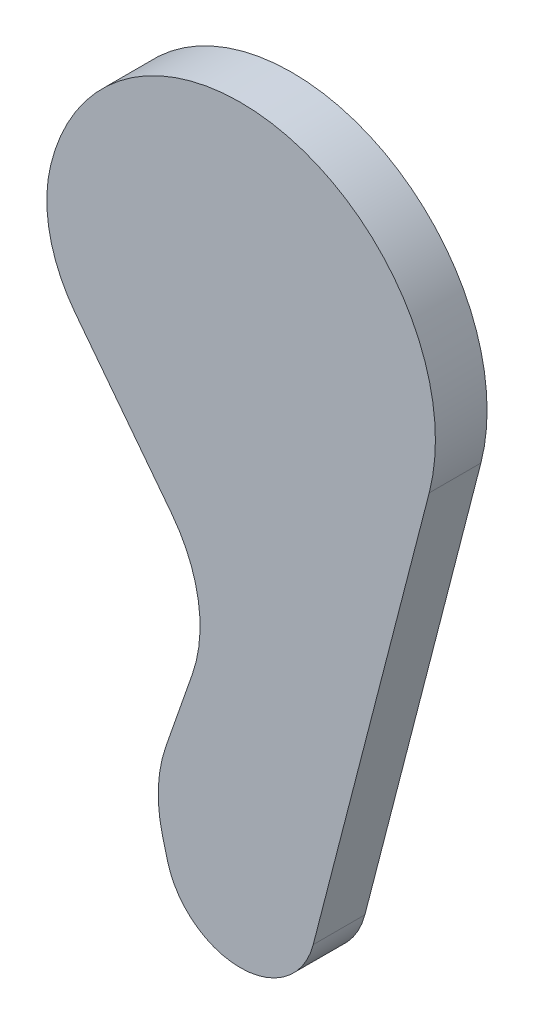
SolidWorks part; units mm, degrees
ref_plane "前视基准面" through (0, 0, 0) normal (0, 0, 1) x (1, 0, 0)
ref_plane "上视基准面" through (0, 0, 0) normal (0, 1, 0) x (1, 0, 0)
ref_plane "右视基准面" through (0, 0, 0) normal (1, 0, 0) x (0, 0, -1)
other "Configuration Table"
sketch "草图1" plane through (0, 0, 0) normal (0, 0, 1) x (1, 0, 0)
  line L0 (-27.595, -7.125) -> (-10.6507, -72.75)
  line L1 (0, 49.9592) -> (0, -157.8901) construction
  line L2 (27.595, -7.125) -> (10.6507, -72.75)
  arc A0 (27.595, -7.125) -> (-27.595, -7.125) centre (0, 0) ccw
  arc A2 (-10.6507, -72.75) -> (10.6507, -72.75) centre (0, -70) ccw
  dimension "D1" = 57
  dimension "D2" = 22
  dimension "D3" = 70
extrude "凸台-拉伸1" add sketch "草图1" along normal blind 3
sketch "草图2" plane through (0, 0, 3) normal (0, 0, 1) x (1, 0, 0)
  line L0 (-12.8723, -64.1457) -> (-3.433, -37.1461)
  line L1 (-27.595, -7.125) -> (-10.6507, -72.75) construction
  line L2 (-3.433, -37.1461) -> (-28.1548, -4.9571)
  line L3 (-12.8723, -64.1457) -> (-28.1548, -4.9571)
extrude "切除-拉伸1" cut sketch "草图2" against normal blind 10
sketch "草图3" plane through (0, 0, 3) normal (0, 0, 1) x (1, 0, 0)
  circle A0 centre (0, -70) radius 11
fillet "圆角2" radius 20 3 edges at (-12.8723, -64.1457, 1.5) (-3.433, -37.1461, 1.5) (-28.0384, -5.1086, 1.5)
sketch "草图4" plane through (0, 0, 0) normal (0, 0, -1) x (-1, 0, 0)
  circle A0 centre (0, -70) radius 11
  circle A1 centre (0, -70) radius 9
  dimension "D1" = 18
extrude "凸台-拉伸2" add sketch "草图4" along normal blind 4.55
sketch "草图5" plane through (0, 0, 0) normal (0, 0, -1) x (-1, 0, 0)
  line L0 (-10.6507, -72.75) -> (-27.595, -7.125) construction
  line L1 (-10.6507, -72.75) -> (-27.595, -7.125)
  line L2 (-10.2954, -66.1263) -> (-25.6585, -6.625)
  line L3 (25.7699, 6.1775) -> (27.7148, 6.6437)
  line L4 (-8.7142, -72.25) -> (-25.6585, -6.625) construction
  arc A0 (27.7148, 6.6437) -> (-27.595, -7.125) centre (0, 0) ccw construction
  arc A1 (27.7148, 6.6437) -> (-27.595, -7.125) centre (0, 0) ccw
  arc A2 (25.7699, 6.1775) -> (-25.6585, -6.625) centre (0, 0) ccw
  circle A3 centre (0, -70) radius 11 construction
  arc A4 (-10.2954, -66.1263) -> (-10.6507, -72.75) centre (0, -70) ccw
  dimension "D1" = 2
extrude "凸台-拉伸3" add sketch "草图5" along normal blind 4.55
